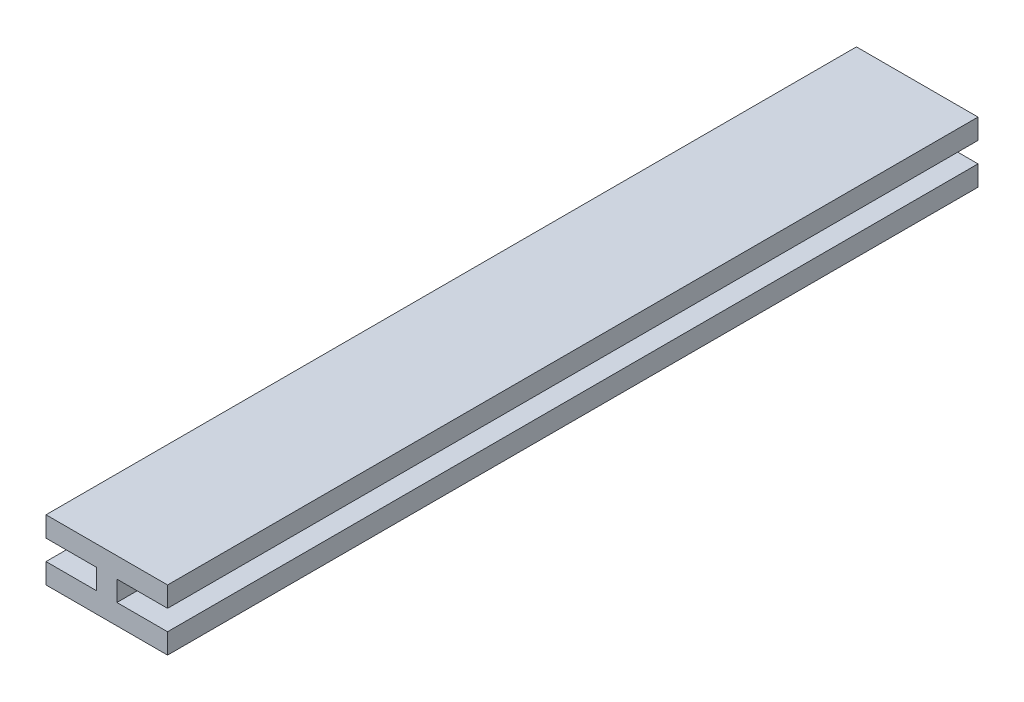
SolidWorks part; units mm, degrees
ref_plane "Front Plane" through (0, 0, 0) normal (0, 0, 1) x (1, 0, 0)
ref_plane "Top Plane" through (0, 0, 0) normal (0, 1, 0) x (1, 0, 0)
ref_plane "Right Plane" through (0, 0, 0) normal (1, 0, 0) x (0, 0, -1)
sketch "Sketch1" plane through (0, 0, 0) normal (0, 1, 0) x (1, 0, 0)
  line L1 (9, -60) -> (-9, -60)
  line L2 (9, -60) -> (9, 60)
  line L3 (9, 60) -> (-9, 60)
  line L4 (-9, -60) -> (-9, 60)
  line L5 (9, -60) -> (-9, 60) construction
  line L6 (9, 60) -> (-9, -60) construction
  point P0 (0, 0)
  dimension "D1" = 18
  dimension "D2" = 120
extrude "Boss-Extrude2" add sketch "Sketch1" along normal blind 3 contours L3 L4 L1 L2
sketch "Sketch4" plane through (0, 3, 0) normal (0, 1, 0) x (1, 0, 0)
  line L0 (9, 60) -> (-9, 60) construction
  line L1 (1.5, -60) -> (-1.5, -60)
  line L2 (1.5, -60) -> (1.5, 60)
  line L3 (1.5, 60) -> (-1.5, 60)
  line L4 (-1.5, -60) -> (-1.5, 60)
  line L5 (1.5, -60) -> (-1.5, 60) construction
  line L6 (1.5, 60) -> (-1.5, -60) construction
  point P0 (0, 0)
  dimension "D1" = 3
extrude "Boss-Extrude3" add sketch "Sketch4" along normal blind 3
sketch "Sketch5" plane through (0, 6, 0) normal (0, 1, 0) x (1, 0, 0)
  line L1 (9, -60) -> (-9, -60)
  line L2 (9, -60) -> (9, 60)
  line L3 (9, 60) -> (-9, 60)
  line L4 (-9, -60) -> (-9, 60)
  line L5 (9, -60) -> (-9, 60) construction
  line L6 (9, 60) -> (-9, -60) construction
  point P0 (0, 0)
  dimension "D1" = 18
  dimension "D2" = 120
extrude "Boss-Extrude4" add sketch "Sketch5" along normal blind 3
